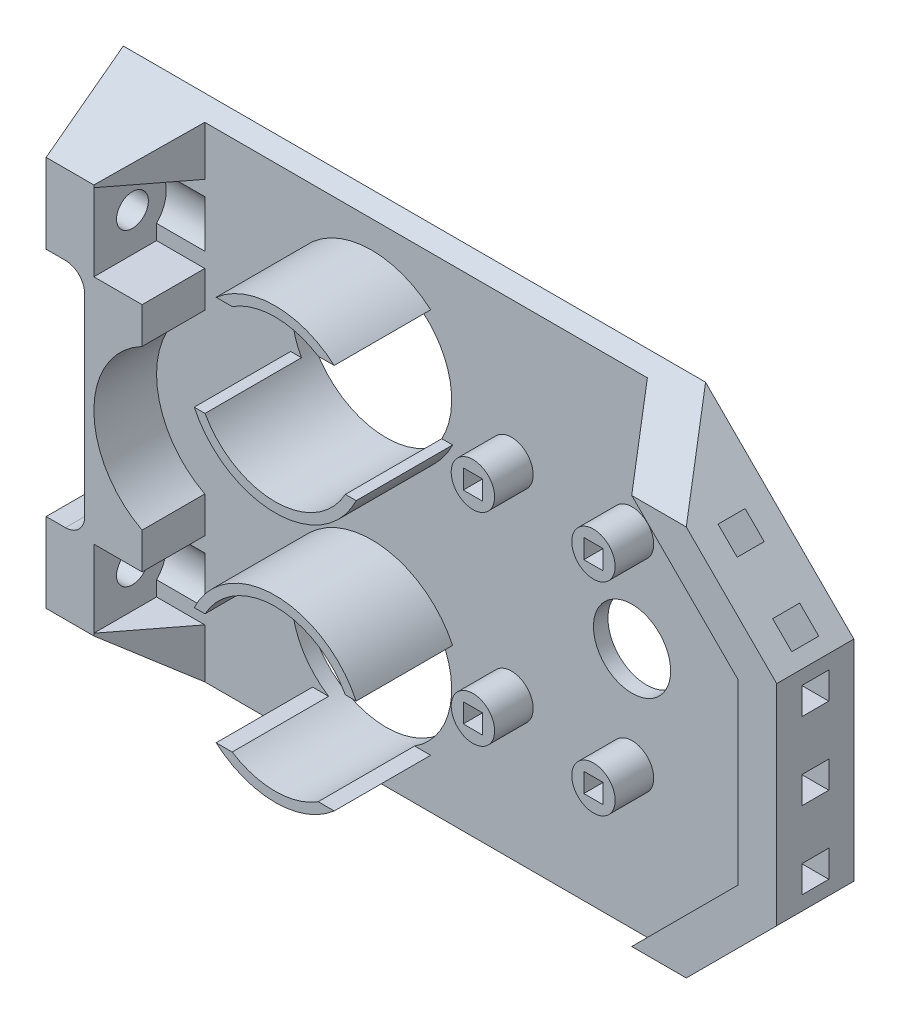
SolidWorks part; units mm, degrees
ref_plane "Plano frontal" through (0, 0, 0) normal (0, 0, 1) x (1, 0, 0)
ref_plane "Plano superior" through (0, 0, 0) normal (0, 1, 0) x (1, 0, 0)
ref_plane "Plano direito" through (0, 0, 0) normal (1, 0, 0) x (0, 0, -1)
sketch "Esboço1" plane through (0, 0, 0) normal (0, 0, 1) x (1, 0, 0)
  line L0 (-5, 0) -> (5, 0) construction
  line L1 (25, 0) -> (-25, 0) construction
  line L2 (0, 0) -> (0, -12.5) construction
  line L3 (25, -12.5) -> (-25, -12.5) construction
  line L4 (-21, 0) -> (-5, 0) construction
  line L5 (-25, -12.5) -> (-25, 12.5)
  line L6 (-25, 12.5) -> (25, 12.5)
  line L7 (0, 12.5) -> (0, 0) construction
  line L8 (20, -12.5) -> (-20, -12.5) construction
  line L12 (-15, -12.5) -> (15, -12.5)
  line L23 (21, 0) -> (5, 0) construction
  line L31 (25, -12.5) -> (25, 12.5)
  line L32 (-25, -12.5) -> (-15, -12.5)
  line L33 (15, -12.5) -> (25, -12.5)
  circle A0 centre (-13, 0) radius 8.3
  circle A1 centre (13, 0) radius 8.3
extrude "Ressalto-extrusão1" add sketch "Esboço1" along normal blind 1.5
sketch "Esboço2" plane through (0, 0, 1.5) normal (0, 0, 1) x (1, 0, 0)
  line L0 (-20, -12.5) -> (-25, -12.5)
  line L1 (0, -12.5) -> (0, 12.5) construction
  line L2 (20, -12.5) -> (-20, -12.5) construction
  line L3 (-25, -12.5) -> (25, -12.5) construction
  line L4 (22, -2.5) -> (22, -9.5)
  line L5 (-25, 12.5) -> (-25, -12.5) construction
  line L6 (-22, -9.5) -> (-15, -9.5)
  line L7 (-15, -9.5) -> (-15, -12.5)
  line L8 (-15, -12.5) -> (-20, -12.5)
  line L9 (-25, -12.5) -> (-25, -2.5)
  line L10 (-25, -2.5) -> (-22, -2.5)
  line L11 (-22, -2.5) -> (-22, -9.5)
  line L12 (25, -2.5) -> (22, -2.5)
  line L13 (25, -12.5) -> (25, -2.5)
  line L14 (15, -12.5) -> (20, -12.5)
  line L15 (25, 12.5) -> (-25, 12.5) construction
  line L16 (15, -9.5) -> (15, -12.5)
  line L17 (-25, 0) -> (25, 0) construction
  line L18 (25, -12.5) -> (25, 12.5) construction
  line L19 (22, -9.5) -> (15, -9.5)
  line L20 (20, -12.5) -> (25, -12.5)
  line L21 (20, 12.5) -> (-20, 12.5) construction
  line L22 (20, 12.5) -> (25, 12.5)
  line L23 (22, 9.5) -> (15, 9.5)
  line L24 (15, 9.5) -> (15, 12.5)
  line L25 (15, 12.5) -> (20, 12.5)
  line L26 (25, 12.5) -> (25, 2.5)
  line L27 (25, 2.5) -> (22, 2.5)
  line L28 (-22, 2.5) -> (-22, 9.5)
  line L29 (-25, 2.5) -> (-22, 2.5)
  line L30 (-25, 12.5) -> (-25, 2.5)
  line L31 (-15, 12.5) -> (-20, 12.5)
  line L32 (-15, 9.5) -> (-15, 12.5)
  line L33 (-22, 9.5) -> (-15, 9.5)
  line L34 (22, 2.5) -> (22, 9.5)
  line L35 (-20, 12.5) -> (-25, 12.5)
extrude "Ressalto-extrusão2" add sketch "Esboço2" along normal blind 6
sketch "Esboço3" plane through (0, -12.5, 0) normal (0, -1, 0) x (1, 0, 0)
  line L0 (-25, 3.75) -> (-15, 3.75) construction
  line L1 (-25, 7.5) -> (-25, 0) construction
  line L2 (-15, 7.5) -> (-15, 1.5) construction
  line L3 (-15, 3.75) -> (-20, 3.75) construction
  line L4 (-20, 3.75) -> (-20, 7.5) construction
  line L5 (-25, 7.5) -> (-15, 7.5) construction
  line L6 (0, 0) -> (0, 8.9122) construction
  line L7 (-21.4, 2.35) -> (-18.6, 2.35)
  line L8 (-21.4, 2.35) -> (-21.4, 5.15)
  line L9 (-21.4, 5.15) -> (-18.6, 5.15)
  line L10 (-18.6, 2.35) -> (-18.6, 5.15)
  line L11 (-21.4, 2.35) -> (-18.6, 5.15) construction
  line L12 (-21.4, 5.15) -> (-18.6, 2.35) construction
  line L13 (-25, 0) -> (25, 0) construction
  line L14 (21.4, 5.15) -> (18.6, 2.35) construction
  line L15 (21.4, 2.35) -> (18.6, 5.15) construction
  line L16 (18.6, 2.35) -> (18.6, 5.15)
  line L17 (21.4, 5.15) -> (18.6, 5.15)
  line L18 (21.4, 2.35) -> (21.4, 5.15)
  line L19 (21.4, 2.35) -> (18.6, 2.35)
extrude "Corte-extrusão1" cut sketch "Esboço3" against normal through all
sketch "Esboço4" plane through (-25, 0, 0) normal (-1, 0, 0) x (0, 0, 1)
  line L2 (3.75, 2.5) -> (3.75, 12.5) construction
  line L5 (3.75, -2.5) -> (3.75, -12.5) construction
  line L9 (0, 12.5) -> (7.5, 12.5) construction
  line L10 (5.15, 8.9) -> (2.35, 8.9)
  line L11 (5.15, 8.9) -> (5.15, 6.1)
  line L12 (5.15, 6.1) -> (2.35, 6.1)
  line L13 (2.35, 8.9) -> (2.35, 6.1)
  line L14 (5.15, 8.9) -> (2.35, 6.1) construction
  line L15 (5.15, 6.1) -> (2.35, 8.9) construction
  line L16 (5.15, -6.1) -> (2.35, -6.1)
  line L17 (5.15, -6.1) -> (5.15, -8.9)
  line L18 (5.15, -8.9) -> (2.35, -8.9)
  line L19 (2.35, -6.1) -> (2.35, -8.9)
  line L20 (5.15, -6.1) -> (2.35, -8.9) construction
  line L21 (5.15, -8.9) -> (2.35, -6.1) construction
  point P12 (3.75, 7.5)
  point P17 (3.75, -7.5)
  point P26 (3.75, 12.5)
extrude "Corte-extrusão2" cut sketch "Esboço4" against normal through all
sketch "Esboço6" plane through (0, 0, 0) normal (0, 0, -1) x (-1, 0, 0)
  line L0 (-25, 12.5) -> (-25, -12.5)
  line L1 (-30, -12.5) -> (-25, -12.5)
  line L2 (-30, -12.5) -> (-30, 12.5)
  line L3 (-30, 12.5) -> (-25, 12.5)
  line L4 (30, -12.5) -> (30, 12.5)
  line L5 (-30, -12.5) -> (30, 12.5) construction
  line L6 (-30, 12.5) -> (30, -12.5) construction
  line L7 (25, 12.5) -> (25, -12.5)
  line L8 (25, 12.5) -> (30, 12.5)
  line L9 (25, -12.5) -> (30, -12.5)
  point P0 (0, 0)
extrude "Ressalto-extrusão5" add sketch "Esboço6" against normal up to surface (7.5 mm away) up to face at (20.6667, -8.1667, 7.5)
sketch "Esboço7" plane through (30, 0, 0) normal (1, 0, 0) x (0, 0, -1)
  line L0 (-2.35, -6.1) -> (-5.15, -6.1) construction
  line L1 (-2.35, -8.9) -> (-2.35, -6.1) construction
  line L2 (-5.15, -8.9) -> (-2.35, -8.9) construction
  line L3 (-5.15, -6.1) -> (-5.15, -8.9) construction
  line L4 (-2.35, -6.1) -> (-5.15, -6.1)
  line L5 (-2.35, -8.9) -> (-2.35, -6.1)
  line L6 (-5.15, -8.9) -> (-2.35, -8.9)
  line L7 (-5.15, -6.1) -> (-5.15, -8.9)
  line L8 (-2.35, 6.1) -> (-2.35, 8.9) construction
  line L9 (-2.35, 8.9) -> (-5.15, 8.9) construction
  line L10 (-5.15, 8.9) -> (-5.15, 6.1) construction
  line L11 (-5.15, 6.1) -> (-2.35, 6.1) construction
  line L12 (-2.35, 6.1) -> (-2.35, 8.9)
  line L13 (-2.35, 8.9) -> (-5.15, 8.9)
  line L14 (-5.15, 8.9) -> (-5.15, 6.1)
  line L15 (-5.15, 6.1) -> (-2.35, 6.1)
extrude "Corte-extrusão3" cut sketch "Esboço7" against normal up to surface (60 mm away) up to face at (-30, 0, 3.75)
sketch "Esboço5" plane through (0, 0, 1.5) normal (0, 0, 1) x (1, 0, 0)
  line L0 (-9, -7.2726) -> (-9, -8.3958)
  line L1 (-17, -7.2726) -> (-17, -8.3958)
  line L2 (-17, 8.3958) -> (-17, 7.2726)
  line L3 (9, -7.2726) -> (9, -8.3958)
  line L4 (-9, 8.3958) -> (-9, 7.2726)
  line L8 (17, 8.3958) -> (17, 7.2726)
  line L10 (9, 8.3958) -> (9, 7.2726)
  line L13 (17, -7.2726) -> (17, -8.3958)
  circle A0 centre (-13, 0) radius 8.3 construction
  circle A1 centre (13, 0) radius 8.3 construction
  arc A2 (-17, 7.2726) -> (-17, -7.2726) centre (-13, 0) ccw
  arc A3 (17, -7.2726) -> (17, 7.2726) centre (13, 0) ccw
  arc A4 (-17, 8.3958) -> (-17, -8.3958) centre (-13, 0) ccw
  arc A5 (17, -8.3958) -> (17, 8.3958) centre (13, 0) ccw
  circle A6 centre (-13, 0) radius 8.3 construction
  circle A7 centre (-13, 0) radius 9.3 construction
  circle A8 centre (13, 0) radius 8.3 construction
  circle A9 centre (13, 0) radius 9.3 construction
  arc A12 (-9, -8.3958) -> (-9, 8.3958) centre (-13, 0) ccw
  arc A13 (-9, -7.2726) -> (-9, 7.2726) centre (-13, 0) ccw
  arc A14 (9, 7.2726) -> (9, -7.2726) centre (13, 0) ccw
  arc A15 (9, 8.3958) -> (9, -8.3958) centre (13, 0) ccw
  dimension "D1" = 1
  dimension "D2" = 1
extrude "Ressalto-extrusão3" add sketch "Esboço5" along normal blind 10
sketch "Esboço8" plane through (0, 0, 0) normal (0, 0, -1) x (-1, 0, 0)
  line L1 (30, 26.25) -> (-30, 26.25)
  line L2 (30, 26.25) -> (30, -26.25)
  line L3 (30, -26.25) -> (-30, -26.25)
  line L4 (-30, 26.25) -> (-30, -26.25)
  line L5 (30, 26.25) -> (-30, -26.25) construction
  line L6 (30, -26.25) -> (-30, 26.25) construction
  circle A0 centre (13, 0) radius 8.3
  circle A1 centre (-13, 0) radius 8.3
  point P6 (0, 0)
extrude "Ressalto-extrusão6" add sketch "Esboço8" against normal blind 1.5
sketch "Esboço9" plane through (0, 0, 1.5) normal (0, 0, 1) x (1, 0, 0)
  line L12 (-15, -12.5) -> (-15, -9.5)
  line L13 (-15, -9.5) -> (-22, -9.5)
  line L14 (-22, -9.5) -> (-22, -2.5)
  line L15 (-22, -2.5) -> (-25, -2.5)
  line L16 (-25, -2.5) -> (-25, 2.5)
  line L17 (-25, 2.5) -> (-22, 2.5)
  line L18 (-22, 2.5) -> (-22, 9.5)
  line L19 (-22, 9.5) -> (-15, 9.5)
  line L20 (-15, 9.5) -> (-15, 12.5)
  line L21 (-15, 12.5) -> (-30, 12.5)
  line L22 (-30, 12.5) -> (-30, -12.5)
  line L23 (-30, -12.5) -> (-15, -12.5)
  line L24 (-15, -12.5) -> (-15, -9.5)
  line L25 (-15, -9.5) -> (-22, -9.5)
  line L26 (-22, -9.5) -> (-22, -2.5)
  line L27 (-22, -2.5) -> (-25, -2.5)
  line L28 (-25, -2.5) -> (-25, 2.5)
  line L29 (-25, 2.5) -> (-22, 2.5)
  line L30 (-22, 2.5) -> (-22, 9.5)
  line L31 (-22, 9.5) -> (-15, 9.5)
  line L32 (-15, 9.5) -> (-15, 12.5)
  line L33 (-15, 12.5) -> (-30, 12.5)
  line L34 (-30, 12.5) -> (-30, -12.5)
  line L35 (-30, -12.5) -> (-15, -12.5)
  dimension "D1" = 0
extrude "Corte-extrusão4" cut sketch "Esboço9" along normal through all
sketch "Esboço10" plane through (0, 0, 1.5) normal (0, 0, 1) x (1, 0, 0)
  line L0 (-24.3, -26.25) -> (-24.3, 26.25)
  line L2 (-24.3, 26.25) -> (-22.3, 26.25)
  line L4 (-22.3, 12) -> (-17.3, 12)
  line L5 (-17.3, 12) -> (-17.3, -12)
  line L6 (-17.3, 0) -> (-24.3, 0) construction
  line L7 (-22.3, 20) -> (-22.3, 12)
  line L8 (-22.3, -20) -> (-22.3, -12)
  line L9 (-22.3, -12) -> (-17.3, -12)
  line L10 (-24.3, -26.25) -> (-22.3, -26.25)
  line L11 (-22.3, 12) -> (-22.3, 16) construction
  line L12 (-22.3, 16) -> (-22.3, 20) construction
  line L13 (-22.3, 20) -> (-17.3, 20)
  line L14 (-17.3, 20) -> (-17.3, 26.25)
  line L15 (-17.3, 26.25) -> (-22.3, 26.25)
  line L16 (-17.3, -26.25) -> (-22.3, -26.25)
  line L17 (-17.3, -20) -> (-17.3, -26.25)
  line L18 (-22.3, -20) -> (-17.3, -20)
  line L19 (-24.3, 0) -> (-22.3, 0) construction
  arc A0 (-17, 8.3958) -> (-17, -8.3958) centre (-13, 0) ccw construction
  point P22 (-22.3, 0)
  dimension "D1" = 12
extrude "Ressalto-extrusão7" add sketch "Esboço10" along normal blind 6.5
sketch "Esboço11" plane through (0, -26.25, 0) normal (0, -1, 0) x (1, 0, 0)
  line L0 (-22.3, 8) -> (-17.3, 8)
  line L1 (-17.3, 8) -> (-17.3, 1.5)
  line L2 (-22.3, 8) -> (-17.3, 1.5)
sketch "Esboço12" plane through (-24.3, 0, 0) normal (-1, 0, 0) x (0, 0, 1)
  line L0 (4, 0) -> (4, 16) construction
  line L1 (0, -26.25) -> (0, 26.25) construction
  line L3 (0, 0) -> (8, 0) construction
  circle A0 centre (4, 16) radius 1.65
  circle A1 centre (4, -16) radius 1.65
  dimension "D1" = 4
sketch "Esboço14" plane through (0, 0, 1.5) normal (0, 0, 1) x (1, 0, 0)
  line L4 (-30, -26.25) -> (-24.3, -26.25)
  line L5 (-24.3, -26.25) -> (-24.3, 26.25)
  line L6 (-24.3, 26.25) -> (-30, 26.25)
  line L7 (-30, 26.25) -> (-30, -26.25)
  line L8 (-30, -26.25) -> (-24.3, -26.25)
  line L9 (-24.3, -26.25) -> (-24.3, 26.25)
  line L10 (-24.3, 26.25) -> (-30, 26.25)
  line L11 (-30, 26.25) -> (-30, -26.25)
  dimension "D1" = 0
extrude "Corte-extrusão8" cut sketch "Esboço14" against normal blind 4.5
sketch "Esboço15" plane through (0, 0, 8) normal (0, 0, 1) x (1, 0, 0)
  line L1 (-17.3, -7.0993) -> (-17.3, 7.0993)
  line L2 (-17.3, -7.0993) -> (-17.3, 7.0993)
  arc A1 (-17.3, 7.0993) -> (-17.3, -7.0993) centre (-13, 0) ccw
  arc A2 (-17.3, 7.0993) -> (-17.3, -7.0993) centre (-13, 0) ccw
  dimension "D1" = 0
extrude "Corte-extrusão9" cut sketch "Esboço15" against normal through all
extrude "Corte-extrusão13" cut sketch "Esboço11" against normal up to surface (6.25 mm away) up to face at (-19.8, -20, 4.75)
sketch "Esboço17" plane through (0, 26.25, 0) normal (0, 1, 0) x (1, 0, 0)
  line L0 (-17.3, -1.5) -> (-17.3, -8)
  line L1 (-17.3, -8) -> (-22.3, -8)
  line L2 (-17.3, -8) -> (-24.3, -8) construction
  line L3 (-22.3, -8) -> (-17.3, -1.5)
extrude "Corte-extrusão14" cut sketch "Esboço17" against normal up to surface (6.25 mm away) up to face at (-19.8, 20, 4.75)
extrude "Corte-extrusão15" cut sketch "Esboço12" against normal blind 4.5
sketch "Esboço19" plane through (-24.3, 0, 0) normal (-1, 0, 0) x (0, 0, 1)
  line L0 (0, 26.25) -> (8, 26.25)
  line L1 (8, 26.25) -> (8, 20.25)
  line L2 (8, 26.25) -> (8, -26.25) construction
  line L3 (8, 20.25) -> (0, 26.25)
  line L4 (0, 0) -> (8, 0) construction
  line L5 (8, -20.25) -> (0, -26.25)
  line L6 (8, -26.25) -> (8, -20.25)
  line L7 (0, -26.25) -> (8, -26.25)
extrude "Corte-extrusão17" cut sketch "Esboço19" against normal through all
sketch "Esboço20" plane through (-22.3, 0, 0) normal (1, 0, 0) x (0, 0, -1)
  circle A0 centre (-4, -16) radius 3.5
  circle A1 centre (-4, 16) radius 3.5
extrude "Corte-extrusão18" cut sketch "Esboço20" along normal blind 5
sketch "Esboço21" plane through (-24.3, 0, 0) normal (-1, 0, 0) x (0, 0, 1)
  line L4 (0, 26.25) -> (0, -26.25)
  line L5 (0, -26.25) -> (8, -20.25)
  line L6 (8, -20.25) -> (8, 20.25)
  line L7 (8, 20.25) -> (0, 26.25)
  line L8 (0, 26.25) -> (0, -26.25)
  line L9 (0, -26.25) -> (8, -20.25)
  line L10 (8, -20.25) -> (8, 20.25)
  line L11 (8, 20.25) -> (0, 26.25)
  circle A0 centre (4, -16) radius 1.65 construction
  circle A1 centre (4, -16) radius 1.65
  circle A2 centre (4, 16) radius 1.65 construction
  circle A3 centre (4, 16) radius 1.65
  dimension "D1" = 0
extrude "Ressalto-extrusão8" add sketch "Esboço21" along normal blind 2.95
sketch "Esboço22" plane through (30, 0, 0) normal (1, 0, 0) x (0, 0, -1)
  line L0 (-2.35, -6.1) -> (-5.15, -6.1) construction
  line L1 (-2.35, -8.9) -> (-2.35, -6.1) construction
  line L2 (-5.15, -8.9) -> (-2.35, -8.9) construction
  line L3 (-5.15, -6.1) -> (-5.15, -8.9) construction
  line L4 (-2.35, 8.9) -> (-5.15, 8.9) construction
  line L5 (-5.15, 8.9) -> (-5.15, 6.1) construction
  line L6 (-2.35, 6.1) -> (-2.35, 8.9) construction
  line L7 (-5.15, 6.1) -> (-2.35, 6.1) construction
  line L8 (-1.5, -25.125) -> (0, -26.25)
  line L9 (0, -26.25) -> (0, 26.25)
  line L10 (0, 26.25) -> (-1.5, 25.125)
  line L11 (-1.5, 25.125) -> (-1.5, 12.5)
  line L12 (-1.5, 12.5) -> (-7.5, 12.5)
  line L13 (-7.5, 12.5) -> (-7.5, -12.5)
  line L14 (-7.5, -12.5) -> (-1.5, -12.5)
  line L15 (-1.5, -12.5) -> (-1.5, -25.125)
  line L16 (-1.5, -25.125) -> (0, -26.25)
  line L17 (0, -26.25) -> (0, 26.25)
  line L18 (0, 26.25) -> (-1.5, 25.125)
  line L19 (-1.5, 25.125) -> (-1.5, 12.5)
  line L20 (-1.5, 12.5) -> (-7.5, 12.5)
  line L21 (-7.5, 12.5) -> (-7.5, -12.5)
  line L22 (-7.5, -12.5) -> (-1.5, -12.5)
  line L23 (-1.5, -12.5) -> (-1.5, -25.125)
  line L24 (-2.35, -6.1) -> (-5.15, -6.1)
  line L25 (-2.35, -8.9) -> (-2.35, -6.1)
  line L26 (-5.15, -8.9) -> (-2.35, -8.9)
  line L27 (-5.15, -6.1) -> (-5.15, -8.9)
  line L28 (-2.35, 8.9) -> (-5.15, 8.9)
  line L29 (-5.15, 8.9) -> (-5.15, 6.1)
  line L30 (-2.35, 6.1) -> (-2.35, 8.9)
  line L31 (-5.15, 6.1) -> (-2.35, 6.1)
  dimension "D1" = 0
extrude "Ressalto-extrusão9" add sketch "Esboço22" along normal blind 1.25
sketch "Esboço23" plane through (0, 0, 7.5) normal (0, 0, 1) x (1, 0, 0)
  line L12 (25, -2.5) -> (22, -2.5)
  line L13 (22, -2.5) -> (22, -9.5)
  line L14 (22, -9.5) -> (15, -9.5)
  line L15 (15, -9.5) -> (15, -12.5)
  line L16 (15, -12.5) -> (31.25, -12.5)
  line L17 (31.25, -12.5) -> (31.25, 12.5)
  line L18 (31.25, 12.5) -> (15, 12.5)
  line L19 (15, 12.5) -> (15, 9.5)
  line L20 (15, 9.5) -> (22, 9.5)
  line L21 (22, 9.5) -> (22, 2.5)
  line L22 (22, 2.5) -> (25, 2.5)
  line L23 (25, 2.5) -> (25, -2.5)
  line L24 (25, -2.5) -> (22, -2.5)
  line L25 (22, -2.5) -> (22, -9.5)
  line L26 (22, -9.5) -> (15, -9.5)
  line L27 (15, -9.5) -> (15, -12.5)
  line L28 (15, -12.5) -> (31.25, -12.5)
  line L29 (31.25, -12.5) -> (31.25, 12.5)
  line L30 (31.25, 12.5) -> (15, 12.5)
  line L31 (15, 12.5) -> (15, 9.5)
  line L32 (15, 9.5) -> (22, 9.5)
  line L33 (22, 9.5) -> (22, 2.5)
  line L34 (22, 2.5) -> (25, 2.5)
  line L35 (25, 2.5) -> (25, -2.5)
  dimension "D1" = 0
extrude "Corte-extrusão19" cut sketch "Esboço23" against normal up to surface (6 mm away) up to face at (13, 0, 1.5)
sketch "Esboço24" plane through (0, 0, 1.5) normal (0, 0, 1) x (1, 0, 0)
  line L0 (31.25, -25.125) -> (-17.3, -25.125) construction
  line L1 (31.25, 25.125) -> (23.25, 25.125)
  line L2 (31.25, 25.125) -> (31.25, -25.125)
  line L3 (31.25, -25.125) -> (23.25, -25.125)
  line L4 (23.25, 25.125) -> (23.25, -25.125)
extrude "Ressalto-extrusão10" add sketch "Esboço24" along normal up to surface (6.5 mm away) up to face at (-21.875, 0, 8)
sketch "Esboço25" plane through (0, 25.125, 0) normal (0, 1, 0) x (1, 0, 0)
  line L1 (23.25, -8) -> (23.25, -1.5) construction
  line L2 (23.25, -6.5) -> (23.25, -8)
  line L3 (23.25, -8) -> (24.75, -8)
  line L4 (23.25, -8) -> (31.25, -8) construction
  line L5 (24.75, -8) -> (23.25, -6.5)
extrude "Corte-extrusão20" cut sketch "Esboço25" against normal through all
sketch "Esboço26" plane through (31.25, 0, 0) normal (1, 0, 0) x (0, 0, -1)
  line L0 (-8, 0) -> (0, 0) construction
  line L1 (-8, 25.125) -> (-8, -25.125) construction
  line L2 (0, 0) -> (-4, 0) construction
  line L3 (-4, 0) -> (-4, -8) construction
  line L4 (-2.6, 1.4) -> (-5.4, 1.4)
  line L5 (-2.6, -6.6) -> (-5.4, -6.6)
  line L6 (-2.6, -6.6) -> (-2.6, -9.4)
  line L7 (-2.6, -9.4) -> (-5.4, -9.4)
  line L8 (-5.4, -6.6) -> (-5.4, -9.4)
  line L9 (-2.6, -6.6) -> (-5.4, -9.4) construction
  line L10 (-2.6, -9.4) -> (-5.4, -6.6) construction
  line L11 (-2.6, 1.4) -> (-2.6, -1.4)
  line L12 (-2.6, -1.4) -> (-5.4, -1.4)
  line L13 (-5.4, 1.4) -> (-5.4, -1.4)
  line L14 (-2.6, 1.4) -> (-5.4, -1.4) construction
  line L15 (-2.6, -1.4) -> (-5.4, 1.4) construction
  line L16 (-2.6, 9.4) -> (-5.4, 9.4)
  line L17 (-2.6, 9.4) -> (-2.6, 6.6)
  line L18 (-2.6, 6.6) -> (-5.4, 6.6)
  line L19 (-5.4, 9.4) -> (-5.4, 6.6)
  line L20 (-2.6, 9.4) -> (-5.4, 6.6) construction
  line L21 (-2.6, 6.6) -> (-5.4, 9.4) construction
  dimension "D1" = 3
extrude "Corte-extrusão21" cut sketch "Esboço26" against normal up to next
sketch "Esboço27" plane through (31.25, 0, 0) normal (1, 0, 0) x (0, 0, -1)
  line L0 (-4, 19) -> (-8, 19)
  line L1 (-8, -20.25) -> (-8, -25.125)
  line L2 (-8, 25.125) -> (-8, -25.125) construction
  line L3 (-8, 25.125) -> (-8, 20.25)
  line L4 (-8, 19) -> (-8, 13)
  line L5 (-8, 13) -> (-4, 13)
  line L6 (-4, -13) -> (-8, -13)
  line L7 (-8, -13) -> (-8, -19)
  line L8 (-8, -19) -> (-4, -19)
  line L9 (-1.5, 25.125) -> (-1.5, -25.125) construction
  line L10 (-1.5, 17.6583) -> (-1.5, 14.3417)
  line L11 (-1.5, -14.3417) -> (-1.5, -17.6583)
  line L13 (-1.5, 25.125) -> (-8, 20.25) construction
  line L17 (-8, -20.25) -> (-1.5, -25.125) construction
  line L21 (-1.5, 25.125) -> (-8, 20.25)
  line L25 (-8, -20.25) -> (-1.5, -25.125)
  line L28 (-1.5, 25.125) -> (-8, 25.125)
  line L30 (-1.5, -25.125) -> (-8, -25.125)
  circle A0 centre (-4, -16) radius 1.65 construction
  circle A1 centre (-4, 16) radius 1.65 construction
  circle A2 centre (-4, -16) radius 1.65 construction
  circle A3 centre (-4, 16) radius 1.65 construction
  arc A4 (-4, -19) -> (-1.5, -17.6583) centre (-4, -16) ccw
  arc A5 (-4, 13) -> (-1.5, 14.3417) centre (-4, 16) ccw
  arc A6 (-1.5, 17.6583) -> (-4, 19) centre (-4, 16) ccw
  arc A7 (-1.5, -14.3417) -> (-4, -13) centre (-4, -16) ccw
extrude "Corte-extrusão22" cut sketch "Esboço27" against normal up to next
sketch "Esboço28" plane through (0, 0, 8) normal (0, 0, 1) x (1, 0, 0)
  line L0 (-27.25, 0) -> (-27.25, 8)
  line L2 (-27.25, -20.25) -> (-27.25, 20.25) construction
  line L3 (-27.25, 8) -> (-27.25, 12)
  line L4 (-27.25, 12) -> (-25.25, 12)
  line L5 (-23.25, 10) -> (-23.25, -10)
  line L6 (-25.25, -12) -> (-27.25, -12)
  line L7 (-27.25, -12) -> (-27.25, 0)
  arc A0 (-25.25, 12) -> (-23.25, 10) centre (-25.25, 10) cw
  arc A1 (-23.25, -10) -> (-25.25, -12) centre (-25.25, -10) cw
  dimension "D1" = 2
extrude "Corte-extrusão23" cut sketch "Esboço28" against normal up to surface (6.5 mm away) up to face at (13, 0, 1.5)
sketch "Esboço31" plane through (0, 0, 1.5) normal (0, 0, 1) x (1, 0, 0)
  line L0 (-9, -7.2726) -> (-9, -8.3958) construction
  line L1 (-9, 8.3958) -> (-9, 7.2726) construction
  line L2 (-17, 7.2726) -> (-17, 8.3958) construction
  line L3 (-17, -8.3958) -> (-17, -7.2726) construction
  line L4 (17, 8.3958) -> (17, 7.2726) construction
  line L5 (17, -7.2726) -> (17, -8.3958) construction
  line L6 (9, -8.3958) -> (9, -7.2726) construction
  line L7 (9, 7.2726) -> (9, 8.3958) construction
  line L8 (-9, -7.2726) -> (-9, -8.3958)
  line L9 (-9, 8.3958) -> (-9, 7.2726)
  line L10 (-17, 7.2726) -> (-17, 8.3958)
  line L11 (-17, -8.3958) -> (-17, -7.2726)
  line L12 (17, 8.3958) -> (17, 7.2726)
  line L13 (17, -7.2726) -> (17, -8.3958)
  line L14 (9, -8.3958) -> (9, -7.2726)
  line L15 (9, 7.2726) -> (9, 8.3958)
  arc A0 (-9, -7.2726) -> (-9, 7.2726) centre (-13, 0) ccw construction
  arc A1 (-9, -8.3958) -> (-9, 8.3958) centre (-13, 0) ccw construction
  arc A2 (-17, 7.2726) -> (-17, -7.2726) centre (-13, 0) ccw construction
  arc A3 (-17, 8.3958) -> (-17, -8.3958) centre (-13, 0) ccw construction
  arc A4 (17, -8.3958) -> (17, 8.3958) centre (13, 0) ccw construction
  arc A5 (17, -7.2726) -> (17, 7.2726) centre (13, 0) ccw construction
  arc A6 (9, 8.3958) -> (9, -8.3958) centre (13, 0) ccw construction
  arc A7 (9, 7.2726) -> (9, -7.2726) centre (13, 0) ccw construction
  arc A8 (-9, -7.2726) -> (-9, 7.2726) centre (-13, 0) ccw
  arc A9 (-9, -8.3958) -> (-9, 8.3958) centre (-13, 0) ccw
  arc A10 (-17, 7.2726) -> (-17, -7.2726) centre (-13, 0) ccw
  arc A11 (-17, 8.3958) -> (-17, -8.3958) centre (-13, 0) ccw
  arc A12 (17, -8.3958) -> (17, 8.3958) centre (13, 0) ccw
  arc A13 (17, -7.2726) -> (17, 7.2726) centre (13, 0) ccw
  arc A14 (9, 8.3958) -> (9, -8.3958) centre (13, 0) ccw
  arc A15 (9, 7.2726) -> (9, -7.2726) centre (13, 0) ccw
extrude "Corte-extrusão24" cut sketch "Esboço31" along normal through all
sketch "Esboço32" plane through (0, 0, 0) normal (0, 0, -1) x (-1, 0, 0)
  circle A0 centre (-13, 0) radius 8.3 construction
  circle A1 centre (13, 0) radius 8.3 construction
  circle A2 centre (-13, 0) radius 8.3
  circle A3 centre (13, 0) radius 8.3
extrude "Ressalto-extrusão11" add sketch "Esboço32" against normal up to surface (1.5 mm away) up to face at (4.7, 0, 1.5)
sketch "Esboço29" plane through (0, 0, 0) normal (0, 0, 1) x (1, 0, 0)
  line L0 (0, -5) -> (0, 5) construction
  line L1 (0, 25) -> (0, -25) construction
  line L2 (0, 0) -> (12.5, 0) construction
  line L3 (12.5, 25) -> (12.5, -25) construction
  line L4 (0, -21) -> (0, -5) construction
  line L5 (12.5, -25) -> (-12.5, -25) construction
  line L6 (-12.5, -25) -> (-12.5, 25) construction
  line L7 (-12.5, 0) -> (0, 0) construction
  line L8 (12.5, 20) -> (12.5, -20) construction
  line L12 (12.5, -15) -> (12.5, 15) construction
  line L23 (0, 21) -> (0, 5) construction
  line L31 (12.5, 25) -> (-12.5, 25) construction
  line L32 (12.5, -25) -> (12.5, -15) construction
  line L33 (12.5, 15) -> (12.5, 25) construction
  circle A0 centre (0, -13) radius 8.3
  circle A1 centre (0, 13) radius 8.3
sketch "Esboço30" plane through (0, 0, 1.5) normal (0, 0, 1) x (1, 0, 0)
  line L0 (7.2726, -9) -> (8.3958, -9)
  line L1 (7.2726, -17) -> (8.3958, -17)
  line L2 (-8.3958, -17) -> (-7.2726, -17)
  line L3 (7.2726, 9) -> (8.3958, 9)
  line L4 (-8.3958, -9) -> (-7.2726, -9)
  line L8 (-8.3958, 17) -> (-7.2726, 17)
  line L10 (-8.3958, 9) -> (-7.2726, 9)
  line L13 (7.2726, 17) -> (8.3958, 17)
  arc A2 (-7.2726, -17) -> (7.2726, -17) centre (0, -13) ccw
  arc A3 (7.2726, 17) -> (-7.2726, 17) centre (0, 13) ccw
  arc A4 (-8.3958, -17) -> (8.3958, -17) centre (0, -13) ccw
  arc A5 (8.3958, 17) -> (-8.3958, 17) centre (0, 13) ccw
  arc A12 (8.3958, -9) -> (-8.3958, -9) centre (0, -13) ccw
  arc A13 (7.2726, -9) -> (-7.2726, -9) centre (0, -13) ccw
  arc A14 (-7.2726, 9) -> (7.2726, 9) centre (0, 13) ccw
  arc A15 (-8.3958, 9) -> (8.3958, 9) centre (0, 13) ccw
extrude "Corte-extrusão27" cut sketch "Esboço29" along normal through all
extrude "Ressalto-extrusão12" add sketch "Esboço30" along normal blind 10
sketch "Esboço36" plane through (0, 0, 1.5) normal (0, 0, 1) x (1, 0, 0)
  line L0 (23.25, -13) -> (23.25, 13) construction
  line L1 (9.7424, 27.9696) -> (36.7576, 27.9696)
  line L2 (9.7424, 27.9696) -> (9.7424, -27.9696)
  line L3 (9.7424, -27.9696) -> (36.7576, -27.9696)
  line L4 (36.7576, 27.9696) -> (36.7576, -27.9696)
  line L5 (9.7424, 27.9696) -> (36.7576, -27.9696) construction
  line L6 (9.7424, -27.9696) -> (36.7576, 27.9696) construction
  point P0 (23.25, 0)
extrude "Corte-extrusão28" cut sketch "Esboço36" along normal blind 10
sketch "Esboço37" plane through (0, 0, 0) normal (0, 0, 1) x (1, 0, 0)
  line L0 (36.5, 0) -> (31, 0) construction
  line L1 (12.5, -12.5) -> (36.5, -12.5) construction
  line L2 (12.5, -12.5) -> (12.5, 12.5) construction
  line L3 (12.5, 12.5) -> (36.5, 12.5) construction
  line L4 (36.5, -12.5) -> (36.5, 12.5) construction
  line L5 (12.5, -12.5) -> (36.5, 12.5) construction
  line L6 (12.5, 12.5) -> (36.5, -12.5) construction
  line L7 (31, 0) -> (27, 0) construction
  line L8 (12.5, -12.5) -> (14.5, -12.5) construction
  line L9 (23, -4) -> (31, -4) construction
  line L10 (23, -4) -> (23, 4) construction
  line L11 (23, 4) -> (31, 4) construction
  line L12 (31, -4) -> (31, 4) construction
  line L13 (23, -4) -> (31, 4) construction
  line L14 (23, 4) -> (31, -4) construction
  line L15 (14.5, -12.5) -> (14.5, -10.5) construction
  line L16 (14.5, -10.5) -> (14.5, 10.5) construction
  line L17 (14.5, -10.5) -> (27, -10.5) construction
  line L18 (14.5, 10.5) -> (27, 10.5) construction
  line L19 (27, -10.5) -> (27, 10.5) construction
  line L20 (13.5, -11.5) -> (13.5, -9.5)
  line L21 (-27.25, 0) -> (0, 0) construction
  line L22 (-27.25, -12) -> (-27.25, 12) construction
  line L23 (0, 0) -> (10, 0) construction
  line L24 (10, 0) -> (27, 0) construction
  line L26 (31.2, -4.2) -> (22.8, -4.2) construction
  line L27 (13.5, -11.5) -> (15.5, -11.5)
  line L28 (13.5, -9.5) -> (15.5, -11.5) construction
  line L29 (13.5, -9.5) -> (15.5, -9.5)
  line L30 (13.5, -11.5) -> (15.5, -9.5) construction
  line L31 (15.5, -11.5) -> (15.5, -9.5)
  line L32 (13.5, 9.5) -> (13.5, 11.5)
  line L33 (13.5, 9.5) -> (15.5, 9.5)
  line L34 (13.5, 11.5) -> (15.5, 9.5) construction
  line L35 (13.5, 11.5) -> (15.5, 11.5)
  line L36 (13.5, 9.5) -> (15.5, 11.5) construction
  line L37 (15.5, 9.5) -> (15.5, 11.5)
  line L38 (26, 9.5) -> (26, 11.5)
  line L39 (26, 9.5) -> (28, 9.5)
  line L40 (26, 11.5) -> (28, 9.5) construction
  line L41 (26, 11.5) -> (28, 11.5)
  line L42 (26, 9.5) -> (28, 11.5) construction
  line L43 (28, 9.5) -> (28, 11.5)
  line L44 (26, -11.5) -> (26, -9.5)
  line L45 (26, -11.5) -> (28, -11.5)
  line L46 (26, -9.5) -> (28, -11.5) construction
  line L47 (26, -9.5) -> (28, -9.5)
  line L48 (26, -11.5) -> (28, -9.5) construction
  line L49 (28, -11.5) -> (28, -9.5)
  line L50 (31.2, -4.2) -> (31.2, 4.2) construction
  line L51 (31.2, 4.2) -> (22.8, 4.2) construction
  line L52 (22.8, -4.2) -> (22.8, 4.2) construction
  line L53 (31.2, -4.2) -> (22.8, 4.2) construction
  line L54 (31.2, 4.2) -> (22.8, -4.2) construction
  circle A0 centre (27, 0) radius 4
  point P0 (24.5, 0)
  point P24 (14.5, -10.5)
  point P29 (14.5, 10.5)
  point P34 (27, 10.5)
  point P39 (27, -10.5)
  point P45 (27, 0)
  dimension "D5" = 8
  dimension "D1" = 5.5
  dimension "D2" = 24
  dimension "D3" = 25
  dimension "D4" = 4
  dimension "D6" = 2
  dimension "D7" = 2
  dimension "D8" = 21
  dimension "D9" = 12.5
  dimension "D10" = 17
  dimension "D11" = 2
  dimension "D12" = 2
  dimension "D13" = 2
  dimension "D14" = 2
  dimension "D15" = 8.4
sketch "Esboço39" plane through (0, 0, 0) normal (0, 0, -1) x (-1, 0, 0)
  line L0 (-36.5, 0) -> (-48.5, 0) construction
  line L1 (-31.25, 26.25) -> (-33.1231, 26.25)
  line L2 (-31.25, 26.25) -> (-31.25, -26.25)
  line L3 (-31.25, -26.25) -> (-33.1231, -26.25)
  line L4 (-33.1231, -26.25) -> (-48.5, -10.8731)
  line L5 (-48.5, -10.8731) -> (-48.5, 10.8731)
  line L6 (-48.5, 10.8731) -> (-33.1231, 26.25)
  line L7 (-31.25, -26.25) -> (-31.25, 26.25) construction
  dimension "D1" = 45
  dimension "D2" = 45
  dimension "D3" = 12
extrude "Ressalto-extrusão13" add sketch "Esboço39" against normal up to surface (1.5 mm away) up to face at (-14.9318, 0, 1.5)
sketch "Esboço40" plane through (0, 0, 1.5) normal (0, 0, 1) x (1, 0, 0)
  circle A0 centre (27, 10.5) radius 2.25
  circle A1 centre (27, -10.5) radius 2.25
  circle A2 centre (14.5, -10.5) radius 2.25
  circle A3 centre (14.5, 10.5) radius 2.25
extrude "Ressalto-extrusão14" add sketch "Esboço40" along normal blind 4
extrude "Corte-extrusão29" cut sketch "Esboço37" along normal through all
sketch "Esboço41" plane through (0, 0, 0) normal (0, 0, -1) x (-1, 0, 0)
  line L0 (-13.5, -11.5) -> (-13.5, -9.5)
  line L1 (-13.5, -9.5) -> (-15.5, -9.5)
  line L2 (-15.5, -9.5) -> (-15.5, -11.5)
  line L3 (-15.5, -11.5) -> (-13.5, -11.5)
  line L4 (-26, -11.5) -> (-28, -11.5)
  line L5 (-28, -11.5) -> (-28, -9.5)
  line L6 (-28, -9.5) -> (-26, -9.5)
  line L7 (-26, -9.5) -> (-26, -11.5)
  line L8 (-26, -11.5) -> (-26.0947, -11.5504)
  line L9 (-28, 11.5) -> (-28, 9.5)
  line L10 (-28, 9.5) -> (-26, 9.5)
  line L11 (-26, 9.5) -> (-26, 11.5)
  line L12 (-26, 11.5) -> (-28, 11.5)
  line L13 (-13.5, 11.5) -> (-15.5, 11.5)
  line L14 (-15.5, 11.5) -> (-15.5, 9.5)
  line L15 (-15.5, 9.5) -> (-13.5, 9.5)
  line L16 (-13.5, 9.5) -> (-13.5, 11.5)
  line M1 (-28, 9.5) -> (-28, 11.5)
  line M2 (-28, 11.5) -> (-26, 11.5)
  line M3 (-26, 11.5) -> (-26, 9.5)
  line M4 (-26, 9.5) -> (-28, 9.5)
  line M5 (-15.5, -11.5) -> (-15.5, -9.5)
  line M6 (-15.5, -9.5) -> (-13.5, -9.5)
  line M7 (-13.5, -9.5) -> (-13.5, -11.5)
  line M8 (-13.5, -11.5) -> (-15.5, -11.5)
  line M20 (-15.5, 9.5) -> (-15.5, 11.5)
  line M21 (-15.5, 11.5) -> (-13.5, 11.5)
  line M22 (-13.5, 11.5) -> (-13.5, 9.5)
  line M23 (-13.5, 9.5) -> (-15.5, 9.5)
  line M24 (-28, -11.5) -> (-28, -9.5)
  line M25 (-28, -9.5) -> (-26, -9.5)
  line M26 (-26, -9.5) -> (-26, -11.5)
  line M27 (-26, -11.5) -> (-28, -11.5)
extrude "Ressalto-extrusão15" add sketch "Esboço41" against normal blind 1 contours M24 M27 M26 M25 | M5 M8 M7 M6 | M20 M23 M22 M21 | M1 M4 M3 M2
sketch "Esboço43" plane through (0, 0, 1.5) normal (0, 0, 1) x (1, 0, 0)
  line L0 (33.1231, 26.25) -> (48.5, 10.8731) construction
  line L1 (48.5, 10.8731) -> (48.5, -10.8731) construction
  line L2 (48.5, -10.8731) -> (33.1231, -26.25) construction
  line L3 (33.1231, 26.25) -> (48.5, 10.8731)
  line L4 (48.5, 10.8731) -> (48.5, -10.8731)
  line L5 (48.5, -10.8731) -> (33.1231, -26.25)
  line L6 (30.2947, 23.4216) -> (44.5, 9.2163)
  line L7 (44.5, 9.2163) -> (44.5, -9.2163)
  line L8 (44.5, -9.2163) -> (30.2947, -23.4216)
  line L9 (30.2947, 23.4216) -> (27.4663, 26.25)
  line L10 (30.2947, -23.4216) -> (27.4663, -26.25)
  line L11 (33.1231, 26.25) -> (27.4663, 26.25)
  line L13 (33.1231, -26.25) -> (27.4663, -26.25)
  dimension "D1" = 4
extrude "Ressalto-extrusão16" add sketch "Esboço43" along normal blind 6.5
sketch "Esboço44" plane through (48.5, 0, 0) normal (1, 0, 0) x (0, 0, -1)
  line L0 (0, 0) -> (-8, 0) construction
  line L1 (-8, -10.8731) -> (-8, 10.8731) construction
  line L2 (-4, 0) -> (-4, 8) construction
  line L3 (-5.4, 1.4) -> (-2.6, 1.4)
  line L4 (-5.4, 1.4) -> (-5.4, -1.4)
  line L5 (-5.4, -1.4) -> (-2.6, -1.4)
  line L6 (-2.6, 1.4) -> (-2.6, -1.4)
  line L7 (-5.4, 1.4) -> (-2.6, -1.4) construction
  line L8 (-5.4, -1.4) -> (-2.6, 1.4) construction
  line L9 (-5.4, 9.4) -> (-2.6, 9.4)
  line L10 (-5.4, 9.4) -> (-2.6, 6.6) construction
  line L11 (-5.4, 6.6) -> (-2.6, 9.4) construction
  line L12 (-5.4, 9.4) -> (-5.4, 6.6)
  line L13 (-2.6, 9.4) -> (-2.6, 6.6)
  line L14 (-5.4, 6.6) -> (-2.6, 6.6)
  line L15 (-5.4, -6.6) -> (-2.6, -9.4) construction
  line L16 (-5.4, -9.4) -> (-2.6, -6.6) construction
  line L17 (-5.4, -6.6) -> (-2.6, -6.6)
  line L18 (-2.6, -9.4) -> (-2.6, -6.6)
  line L19 (-5.4, -9.4) -> (-5.4, -6.6)
  line L20 (-5.4, -9.4) -> (-2.6, -9.4)
  point P5 (-4, 0)
  point P12 (-4, 8)
  point P21 (-4, -8)
  dimension "D1" = 2.8
  dimension "D2" = 2.8
extrude "Corte-extrusão30" cut sketch "Esboço44" against normal blind 12.5
sketch "Esboço45" plane through (29.6866, -29.6866, 0) normal (0.7071, -0.7071, 0) x (0, 0, -1)
  line L0 (-4, 26.6062) -> (-4, 4.86) construction
  line L1 (-8, 26.6062) -> (0, 26.6062) construction
  line L2 (-8, 4.86) -> (0, 4.86) construction
  line L3 (-4, 15.7331) -> (-4, 23.7331) construction
  line L4 (-4, 15.7331) -> (-4, 7.7331) construction
  line L11 (0, 15.7331) -> (-4, 15.7331) construction
  line L12 (0, 26.6062) -> (0, 4.86) construction
  line L13 (-5.4, 25.1331) -> (-2.6, 25.1331)
  line L14 (-5.4, 22.3331) -> (-2.6, 25.1331) construction
  line L15 (-2.6, 25.1331) -> (-2.6, 22.3331)
  line L16 (-5.4, 25.1331) -> (-2.6, 22.3331) construction
  line L17 (-5.4, 22.3331) -> (-2.6, 22.3331)
  line L18 (-5.4, 25.1331) -> (-5.4, 22.3331)
  line L19 (-5.4, 17.1331) -> (-2.6, 17.1331)
  line L20 (-5.4, 14.3331) -> (-2.6, 17.1331) construction
  line L21 (-2.6, 17.1331) -> (-2.6, 14.3331)
  line L22 (-5.4, 17.1331) -> (-2.6, 14.3331) construction
  line L23 (-5.4, 14.3331) -> (-2.6, 14.3331)
  line L24 (-5.4, 17.1331) -> (-5.4, 14.3331)
  point P15 (-4, 23.7331)
  point P22 (-4, 15.7331)
  dimension "D2" = 8
  dimension "D3" = 8
  dimension "D4" = 2.8
  dimension "D5" = 2.8
extrude "Corte-extrusão31" cut sketch "Esboço45" against normal blind 5.5
sketch "Esboço46" plane through (29.6866, 29.6866, 0) normal (0.7071, 0.7071, 0) x (0, 0, -1)
  line L0 (-4, -26.6062) -> (-4, -4.86) construction
  line L1 (-8, -26.6062) -> (0, -26.6062) construction
  line L2 (-8, -4.86) -> (0, -4.86) construction
  line L3 (-4, -15.7331) -> (-4, -23.7331) construction
  line L4 (-4, -23.7331) -> (-4, -7.7331) construction
  line L17 (-5.4, -17.1331) -> (-2.6, -17.1331)
  line L18 (-5.4, -14.3331) -> (-2.6, -17.1331) construction
  line L19 (-2.6, -14.3331) -> (-2.6, -17.1331)
  line L20 (-5.4, -17.1331) -> (-2.6, -14.3331) construction
  line L21 (-5.4, -14.3331) -> (-5.4, -17.1331)
  line L22 (-5.4, -14.3331) -> (-2.6, -14.3331)
  line L23 (-5.4, -25.1331) -> (-2.6, -25.1331)
  line L24 (-5.4, -22.3331) -> (-2.6, -25.1331) construction
  line L25 (-2.6, -22.3331) -> (-2.6, -25.1331)
  line L26 (-5.4, -25.1331) -> (-2.6, -22.3331) construction
  line L27 (-5.4, -22.3331) -> (-5.4, -25.1331)
  line L28 (-5.4, -22.3331) -> (-2.6, -22.3331)
  point P19 (-4, -15.7331)
  point P24 (-4, -23.7331)
  dimension "D1" = 8
  dimension "D2" = 8
  dimension "D5" = 2.8
  dimension "D6" = 2.8
extrude "Corte-extrusão32" cut sketch "Esboço46" against normal blind 5.5
sketch "Esboço48" plane through (-27.25, 0, 0) normal (-1, 0, 0) x (0, 0, 1)
  line L0 (8, 20.25) -> (0, 26.25) construction
  line L1 (0, -26.25) -> (8, -20.25) construction
  line L2 (8, 20.25) -> (0, 26.25)
  line L3 (0, -26.25) -> (8, -20.25)
  line L4 (8, 20.25) -> (17.9756, 20.25)
  line L5 (17.9756, 20.25) -> (17.9756, 28.8936)
  line L6 (17.9756, 28.8936) -> (0, 28.8936)
  line L7 (0, 28.8936) -> (0, 26.25)
  line L8 (0, -26.25) -> (0, -29.6755)
  line L9 (0, -29.6755) -> (14.9192, -29.6755)
  line L10 (14.9192, -29.6755) -> (14.9192, -20.25)
  line L11 (14.9192, -20.25) -> (8, -20.25)
extrude "Corte-extrusão33" cut sketch "Esboço48" against normal blind 45.5 from offset 40 offset against normal yes
sketch "Esboço49" plane through (0, 0, 1.5) normal (0, 0, 1) x (1, 0, 0)
  line L0 (-22.3, 12) -> (-17.3, 12) construction
  line L1 (-17.3, 12) -> (-17.3, -12) construction
  line L2 (-17.3, -12) -> (-22.3, -12) construction
  line L4 (-22.3, 20) -> (10.2288, 20)
  line L5 (-22.3, 20) -> (-22.3, 12)
  line L6 (-22.3, 12) -> (10.2288, 12)
  line L7 (10.2288, 20) -> (10.2288, 12)
  line L8 (-22.3, -20) -> (10.2288, -20)
  line L9 (-22.3, -20) -> (-22.3, -12)
  line L10 (-22.3, -12) -> (10.2288, -12)
  line L11 (10.2288, -20) -> (10.2288, -12)
extrude "Corte-extrusão34" cut sketch "Esboço49" along normal blind 15.5
